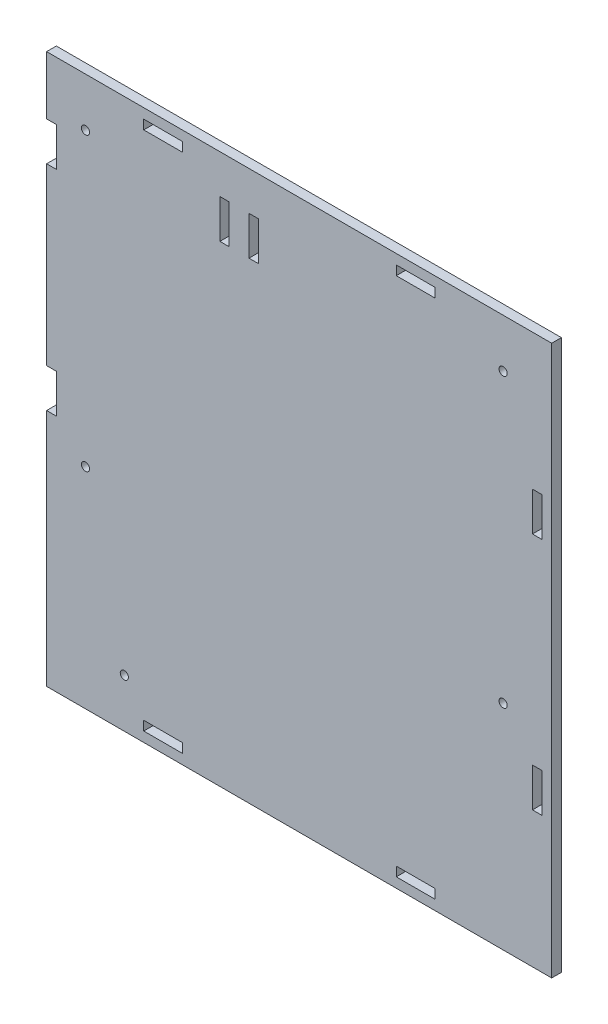
SolidWorks part; units mm, degrees
material "Acrylic (Medium-high impact)"
ref_plane "Front Plane" through (0, 0, 0) normal (0, 0, 1) x (1, 0, 0)
ref_plane "Top Plane" through (0, 0, 0) normal (0, 1, 0) x (1, 0, 0)
ref_plane "Right Plane" through (0, 0, 0) normal (1, 0, 0) x (0, 0, -1)
sketch "Sketch1" plane through (0, 0, 0) normal (0, 0, 1) x (1, 0, 0)
  line L0 (5, 278) -> (5, 208) construction
  line L1 (-250, -5) -> (10, -5)
  line L2 (-250, -5) -> (-250, 278)
  line L3 (-250, 278) -> (10, 278)
  line L4 (10, -5) -> (10, 278)
  line L5 (5, 278) -> (0, 278) construction
  line L6 (-200, 0) -> (-200, 5) construction
  line L7 (-200, 4.9) -> (-180, 4.9)
  line L8 (-200, 4.9) -> (-200, 0.1)
  line L9 (-200, 0.1) -> (-180, 0.1)
  line L10 (-180, 4.9) -> (-180, 0.1)
  line L11 (-180, 0) -> (-180, 5) construction
  line L12 (-70, 0) -> (-70, 5) construction
  line L13 (-70, 4.9) -> (-50, 4.9)
  line L14 (-70, 4.9) -> (-70, 0.1)
  line L15 (-70, 0.1) -> (-50, 0.1)
  line L16 (-50, 4.9) -> (-50, 0.1)
  line L17 (-50, 0) -> (-50, 5) construction
  line L18 (0, 85) -> (5, 85) construction
  line L19 (0.1, 85) -> (4.9, 85)
  line L20 (0.1, 85) -> (0.1, 65)
  line L21 (0.1, 65) -> (4.9, 65)
  line L22 (4.9, 85) -> (4.9, 65)
  line L23 (0, 65) -> (5, 65) construction
  line L24 (0, 65) -> (0, 85) construction
  line L25 (0, 208) -> (5, 208) construction
  line L26 (0.1, 208) -> (4.9, 208)
  line L27 (0.1, 208) -> (0.1, 188)
  line L28 (0.1, 188) -> (4.9, 188)
  line L29 (4.9, 208) -> (4.9, 188)
  line L30 (0, 208) -> (5, 208) construction
  line L31 (0, 188) -> (5, 188) construction
  line L32 (0, 188) -> (0, 208) construction
  line L33 (-70, 273) -> (-70, 268) construction
  line L34 (-70, 272.9) -> (-50, 272.9)
  line L35 (-70, 272.9) -> (-70, 268.1)
  line L36 (-70, 268.1) -> (-50, 268.1)
  line L37 (-50, 272.9) -> (-50, 268.1)
  line L38 (-50, 273) -> (-50, 268) construction
  line L39 (-70, 268) -> (-50, 268) construction
  line L40 (-200, 273) -> (-200, 268) construction
  line L41 (-200, 272.9) -> (-180, 272.9)
  line L42 (-200, 272.9) -> (-200, 268.1)
  line L43 (-200, 268.1) -> (-180, 268.1)
  line L44 (-180, 272.9) -> (-180, 268.1)
  line L45 (-180, 273) -> (-180, 268) construction
  line L46 (-200, 268) -> (-180, 268) construction
  line L47 (5, -5) -> (0, -5) construction
  line L48 (-250, 5) -> (-250, 0) construction
  dimension "D1" = 5
  dimension "D2" = 4.8
  dimension "D3" = 5.1
  dimension "D4" = 4.8
  dimension "D5" = 5.1
  dimension "D6" = 4.8
  dimension "D7" = 0.1
  dimension "D8" = 4.8
  dimension "D9" = 0.1
  dimension "D10" = 4.8
  dimension "D11" = 0.1
  dimension "D12" = 4.8
  dimension "D13" = 0.1
extrude "Boss-Extrude1" add sketch "Sketch1" along normal blind 5
sketch "Sketch2" plane through (0, 0, 5) normal (0, 0, 1) x (1, 0, 0)
  line L0 (-145.9052, 258) -> (-140.9052, 258) construction
  line L1 (-145.8052, 258) -> (-141.0052, 258)
  line L2 (-145.8052, 258) -> (-145.8052, 238)
  line L3 (-145.8052, 238) -> (-141.0052, 238)
  line L4 (-141.0052, 258) -> (-141.0052, 238)
  line L5 (-145.9052, 238) -> (-140.9052, 238) construction
  line L6 (-145.9052, 238) -> (-145.9052, 258) construction
  line L8 (-156.0052, 238) -> (-160.8052, 238)
  line L9 (-156.0052, 238) -> (-156.0052, 258)
  line L10 (-156.0052, 258) -> (-160.8052, 258)
  line L11 (-160.8052, 238) -> (-160.8052, 258)
  dimension "D1" = 4.8
  dimension "D2" = 0.1
  dimension "D3" = 4.8
  dimension "D4" = 15
extrude "Cut-Extrude1" cut sketch "Sketch2" against normal blind 5
sketch "Sketch3" plane through (0, 0, 5) normal (0, 0, 1) x (1, 0, 0)
  line L0 (10, 278) -> (-250, 278) construction
  line L1 (-250, 278) -> (-250, -5) construction
  line L2 (10, -5) -> (10, 278) construction
  circle A0 centre (-230, 253) radius 2.1
  circle A1 centre (-15, 253) radius 2.1
  dimension "D1" = 4.2
  dimension "D2" = 4.2
  dimension "D3" = 25
  dimension "D4" = 20
  dimension "D5" = 25
  dimension "D6" = 25
extrude "Cut-Extrude2" cut sketch "Sketch3" against normal blind 5
sketch "Sketch4" plane through (0, 0, 5) normal (0, 0, 1) x (1, 0, 0)
  line L0 (-250, -5) -> (10, -5) construction
  line L1 (-250, 278) -> (-250, -5) construction
  circle A0 centre (-210, 20) radius 2.1
  dimension "D1" = 25
  dimension "D2" = 40
  dimension "D3" = 4.2
extrude "Cut-Extrude3" cut sketch "Sketch4" against normal blind 5
sketch "Sketch5" plane through (0, 0, 5) normal (0, 0, 1) x (1, 0, 0)
  line L0 (10, -5) -> (10, 278) construction
  line L1 (-250, -5) -> (10, -5) construction
  circle A0 centre (-15, 105) radius 2.1
  dimension "D1" = 4.2
  dimension "D2" = 25
  dimension "D3" = 110
extrude "Cut-Extrude4" cut sketch "Sketch5" against normal blind 5
sketch "Sketch6" plane through (0, 0, 5) normal (0, 0, 1) x (1, 0, 0)
  circle A0 centre (-230, 103) radius 2.1
  dimension "D1" = 4.2
extrude "Cut-Extrude5" cut sketch "Sketch6" against normal blind 5
sketch "Sketch7" plane through (0, 0, 5) normal (0, 0, 1) x (1, 0, 0)
  line L1 (-250, 248) -> (-245, 248)
  line L2 (-250, 248) -> (-250, 228)
  line L3 (-250, 228) -> (-245, 228)
  line L4 (-245, 248) -> (-245, 228)
  line L5 (-250, 138) -> (-245, 138)
  line L6 (-250, 138) -> (-250, 118)
  line L7 (-250, 118) -> (-245, 118)
  line L8 (-245, 138) -> (-245, 118)
  dimension "D1" = 20
  dimension "D2" = 5
  dimension "D3" = 5
  dimension "D4" = 20
extrude "Cut-Extrude6" cut sketch "Sketch7" against normal blind 10
